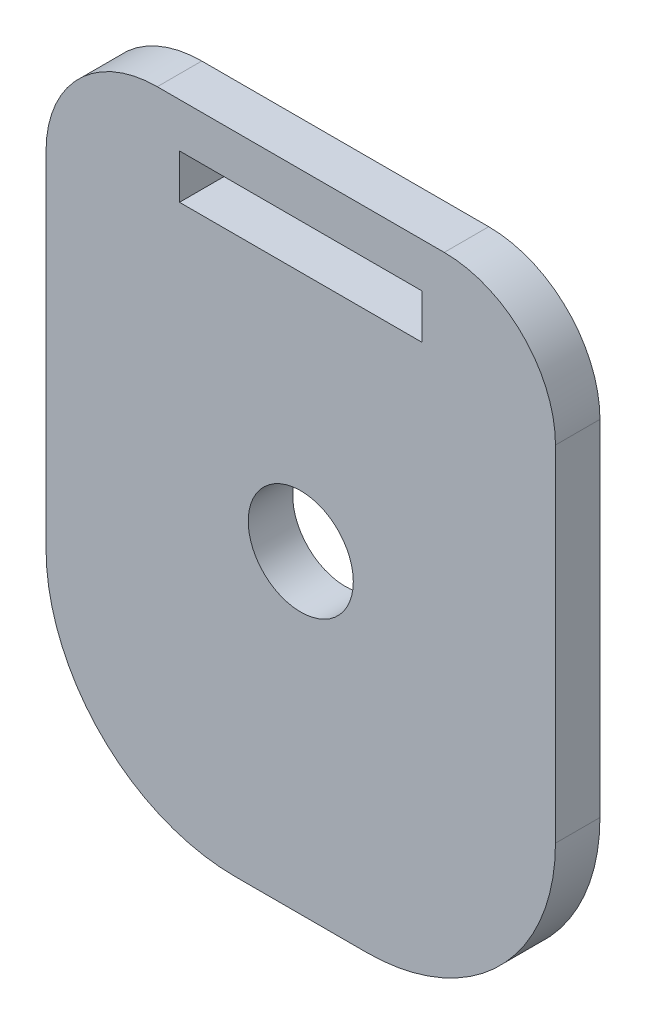
SolidWorks part; units mm, degrees
ref_plane "Front Plane" through (0, 0, 0) normal (0, 0, 1) x (1, 0, 0)
ref_plane "Top Plane" through (0, 0, 0) normal (0, 1, 0) x (1, 0, 0)
ref_plane "Right Plane" through (0, 0, 0) normal (1, 0, 0) x (0, 0, -1)
sketch "Sketch1" plane through (0, 0, 0) normal (0, 0, 1) x (1, 0, 0)
  line L0 (0, 58.42) -> (58.166, 58.42) construction
  line L1 (0, 0) -> (58.166, 0)
  line L2 (0, 0) -> (0, 73.66)
  line L3 (0, 73.66) -> (58.166, 73.66)
  line L4 (58.166, 0) -> (58.166, 73.66)
  dimension "D1" = 73.66
  dimension "D2" = 58.166
  dimension "D3" = 15.24
extrude "Boss-Extrude1" add sketch "Sketch1" along normal blind 5.08
sketch "Sketch2" plane through (0, 0, 5.08) normal (0, 0, 1) x (1, 0, 0)
  line L0 (0, 58.42) -> (58.166, 58.42) construction
  line L1 (0, 73.66) -> (0, 0) construction
  line L2 (58.166, 0) -> (58.166, 73.66) construction
  line L4 (15.24, 68.58) -> (42.926, 68.58)
  line L5 (15.24, 68.58) -> (15.24, 63.5)
  line L6 (15.24, 63.5) -> (42.926, 63.5)
  line L7 (42.926, 68.58) -> (42.926, 63.5)
  line L8 (0, 66.04) -> (15.24, 66.04) construction
  line L9 (42.926, 66.04) -> (58.166, 66.04) construction
  dimension "D1" = 15.24
  dimension "D2" = 5.08
  dimension "D4" = 5.08
  dimension "D3" = 15.24
  dimension "D5" = 27.686
extrude "Cut-Extrude1" cut sketch "Sketch2" against normal through all
sketch "Sketch7" plane through (0, 0, 5.08) normal (0, 0, 1) x (1, 0, 0)
  line L1 (0, 73.66) -> (0, 0) construction
  line L2 (58.166, 0) -> (58.166, 73.66) construction
  line L3 (58.166, 73.66) -> (0, 73.66) construction
  line L4 (0, 28.9) -> (58.166, 28.9) construction
  line L5 (0, 0) -> (58.166, 0) construction
  line L6 (29.083, 73.66) -> (29.083, 0) construction
  circle A0 centre (29.083, 35.9) radius 6
  circle A2 centre (29.083, 28.9) radius 15.5 construction
  circle A4 centre (13.583, 28.9) radius 2
  circle A5 centre (44.583, 28.9) radius 2
  circle A6 centre (37.2492, 15.7257) radius 2
  dimension "D1" = 12
  dimension "D3" = 31
  dimension "D2" = 4
  dimension "D4" = 28.9
  dimension "D5" = 7
extrude "Cut-Extrude2" cut sketch "Sketch7" against normal through all contours A0
fillet "Fillet1" radius 21.59 2 edges at (58.166, 0, 2.54) (0, 0, 2.54)
fillet "Fillet2" radius 12.7 2 edges at (58.166, 73.66, 2.54) (0, 73.66, 2.54)
equation "\"MDF\"= .2"
equation "\"Foamcore\"= .1"
equation "\"GMaterial\"= \"MDF\""
equation "\"CutDistance\" = .1"
equation "\"D1@Boss-Extrude1\"=\"GMaterial\""
equation "\"D1@Sketch1\"=3*\"GMaterial\" + 2.30"
equation "\"D1@Sketch2\"=3*\"GMaterial\""
equation "\"D2@Sketch2\"=\"GMaterial\""
equation "\"D4@Sketch2\"=\"GMaterial\""
equation "\"G\"=0.857891"
equation "\"D3@Sketch1\"=\"GMaterial\" * 3"
